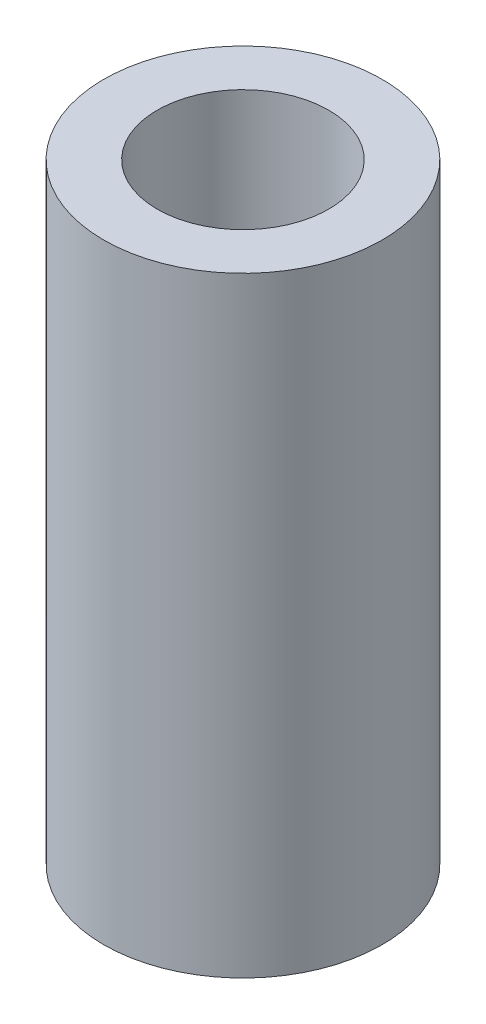
SolidWorks part; units mm, degrees
ref_plane "前视基准面" through (0, 0, 0) normal (0, 0, 1) x (1, 0, 0)
ref_plane "上视基准面" through (0, 0, 0) normal (0, 1, 0) x (1, 0, 0)
ref_plane "右视基准面" through (0, 0, 0) normal (1, 0, 0) x (0, 0, -1)
other "Configuration Table"
sketch "草图1" plane through (0, 0, 0) normal (0, 1, 0) x (1, 0, 0)
  circle A0 centre (0, 0) radius 3.05
  circle A1 centre (0, 0) radius 4.95
  dimension "D1" = 6.1
  dimension "D2" = 9.9
extrude "凸台-拉伸1" add sketch "草图1" along normal blind 21.7
